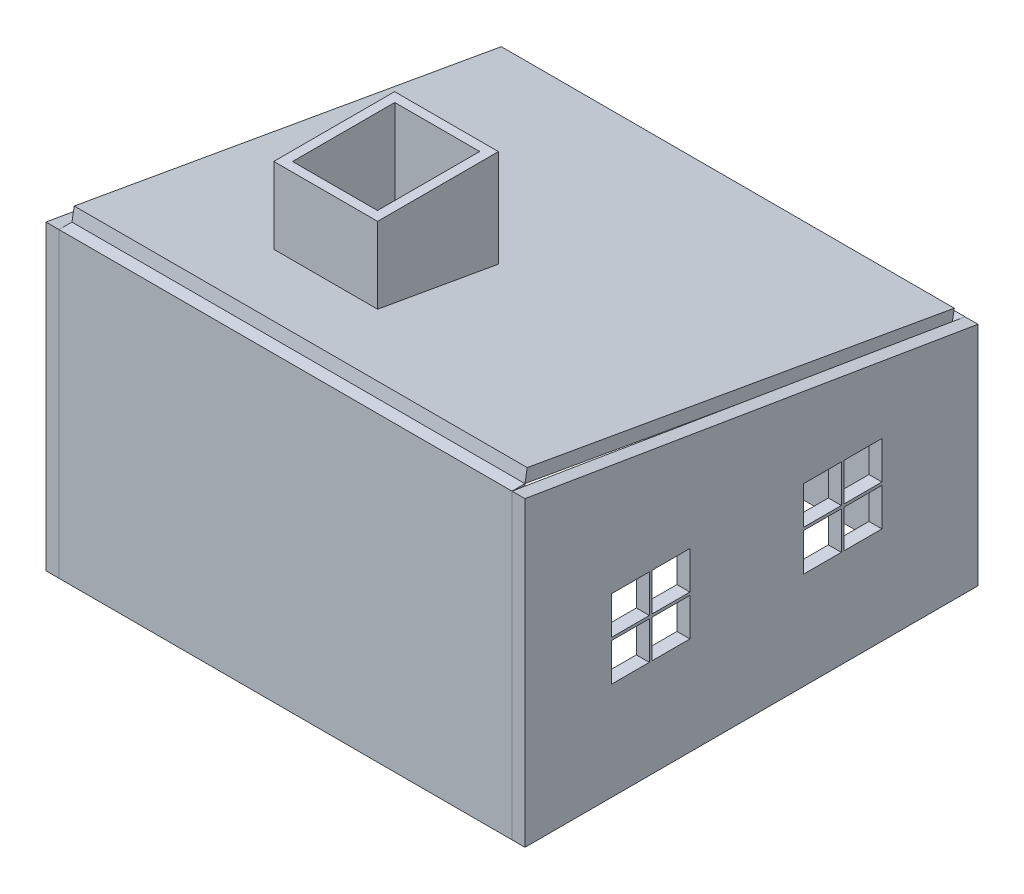
SolidWorks part; units mm, degrees
ref_plane "Front Plane" through (0, 0, 0) normal (0, 0, 1) x (1, 0, 0)
ref_plane "Top Plane" through (0, 0, 0) normal (0, 1, 0) x (1, 0, 0)
ref_plane "Right Plane" through (0, 0, 0) normal (1, 0, 0) x (0, 0, -1)
sketch "Sketch2" plane through (0, 0, 0) normal (0, 1, 0) x (1, 0, 0)
  line L1 (304.8, -287.3375) -> (-304.8, -287.3375)
  line L2 (304.8, -287.3375) -> (304.8, 287.3375)
  line L3 (304.8, 287.3375) -> (-304.8, 287.3375)
  line L4 (-304.8, -287.3375) -> (-304.8, 287.3375)
  line L5 (304.8, -287.3375) -> (-304.8, 287.3375) construction
  line L6 (304.8, 287.3375) -> (-304.8, -287.3375) construction
  point P0 (0, 0)
  dimension "D1" = 609.6
  dimension "D2" = 574.675
ref_plane "Plane1" through (-304.8, 0, 0) normal (1, 0, 0) x (0, 0, -1)
ref_plane "Plane2" through (0, 0, 287.3375) normal (0, 0, 1) x (1, 0, 0)
ref_plane "Plane3" through (304.8, 0, 0) normal (1, 0, 0) x (0, 0, -1)
ref_plane "Plane4" through (0, 0, -287.3375) normal (0, 0, 1) x (1, 0, 0)
sketch "Sketch4" plane through (0, 0, -287.3375) normal (0, 0, 1) x (1, 0, 0)
  line L1 (304.8, 0) -> (-304.8, 0)
  line L2 (304.8, 0) -> (304.8, 304.8)
  line L3 (304.8, 304.8) -> (-304.8, 304.8)
  line L4 (-304.8, 0) -> (-304.8, 304.8)
  dimension "D1" = 304.8
  dimension "D2" = 609.6
extrude "Boss-Extrude2" add sketch "Sketch4" against normal blind 17.4625 separate body contours L3 L4 L1 L2
sketch "Sketch5" plane through (-304.8, 0, 0) normal (1, 0, 0) x (0, 0, -1)
  line L1 (304.8, 0) -> (-304.8, 0)
  line L2 (304.8, 0) -> (304.8, 304.8)
  line L3 (304.8, 304.8) -> (-304.8, 406.4)
  line L4 (-304.8, 0) -> (-304.8, 406.4)
  dimension "D1" = 304.8
  dimension "D2" = 609.6
  dimension "D3" = 406.4
extrude "Boss-Extrude3" add sketch "Sketch5" against normal blind 17.4625 separate body
sketch "Sketch6" plane through (0, 0, 287.3375) normal (0, 0, 1) x (1, 0, 0)
  line L1 (-304.8, 0) -> (304.8, 0)
  line L2 (-304.8, 0) -> (-304.8, 406.4)
  line L3 (-304.8, 406.4) -> (304.8, 406.4)
  line L4 (304.8, 0) -> (304.8, 406.4)
  dimension "D1" = 609.6
  dimension "D2" = 406.4
extrude "Boss-Extrude4" add sketch "Sketch6" along normal blind 17.4625 separate body
sketch "Sketch3" plane through (304.8, 0, 0) normal (1, 0, 0) x (0, 0, -1)
  line L1 (-304.8, 0) -> (304.8, 0)
  line L2 (-304.8, 0) -> (-304.8, 406.4)
  line L3 (-304.8, 406.4) -> (304.8, 304.8)
  line L4 (304.8, 0) -> (304.8, 304.8)
  dimension "D1" = 304.8
  dimension "D2" = 609.6
extrude "Boss-Extrude1" add sketch "Sketch3" along normal blind 17.4625 separate body
ref_plane "Plane5" through (0, 344.822, -60.963) normal (0, -0.9847, 0.1741) x (-1, 0, 0)
sketch "Sketch7" plane through (0, 344.822, -60.963) normal (0, -0.9847, 0.1741) x (-1, 0, 0)
  line L0 (-304.8, 229.8851) -> (304.8, 229.8851) construction
  line L1 (304.8, -353.702) -> (-304.8, -353.702)
  line L2 (304.8, -353.702) -> (304.8, 229.8851)
  line L3 (304.8, 229.8851) -> (-304.8, 229.8851)
  line L4 (-304.8, -353.702) -> (-304.8, 229.8851)
  line L6 (-304.8, -353.702) -> (304.8, -353.702) construction
  line L7 (304.8, 229.8851) -> (0, 51.2594) construction
  line L8 (0, 51.2594) -> (-304.8, 229.8851) construction
  line L9 (0, 229.8851) -> (0, 51.2594) construction
  line L10 (0, -61.7545) -> (0, 229.8851) construction
  dimension "D1" = 609.6
extrude "Boss-Extrude6" add sketch "Sketch7" against normal blind 17.4625 separate body
ref_plane "Plane6" through (0, 508, 0) normal (0, 1, 0) x (1, 0, 0)
sketch "Sketch8" plane through (0, 362.0178, -64.0032) normal (0, 0.9847, -0.1741) x (1, 0, 0)
  line L0 (304.8, -370.8978) -> (-304.8, -370.8978) construction
  line L1 (-11.1125, -237.5478) -> (-125.4125, -237.5478)
  line L2 (-11.1125, -237.5478) -> (-11.1125, -97.8478)
  line L3 (-11.1125, -97.8478) -> (-125.4125, -97.8478)
  line L4 (-125.4125, -237.5478) -> (-125.4125, -97.8478)
  line L5 (-11.1125, -237.5478) -> (-125.4125, -97.8478) construction
  line L6 (-11.1125, -97.8478) -> (-125.4125, -237.5478) construction
  line L7 (1.5875, -85.1478) -> (-138.1125, -85.1478)
  line L8 (1.5875, -85.1478) -> (1.5875, -250.2478)
  line L9 (1.5875, -250.2478) -> (-138.1125, -250.2478)
  line L10 (-138.1125, -85.1478) -> (-138.1125, -250.2478)
  line L11 (1.5875, -85.1478) -> (-138.1125, -250.2478) construction
  line L12 (1.5875, -250.2478) -> (-138.1125, -85.1478) construction
  line L13 (-322.2625, 247.081) -> (-322.2625, -370.8978) construction
  point P0 (-68.2625, -167.6978)
  point P5 (-68.2625, -167.6978)
  dimension "D1" = 12.7
  dimension "D2" = 12.7
  dimension "D3" = 203.2
  dimension "D4" = 254
  dimension "D5" = 139.7
  dimension "D6" = 165.1
extrude "Boss-Extrude7" add sketch "Sketch8" along direction (0, 1, 0) on the side of the normal up to surface (104.6261 mm away) separate body up to plane "Plane6"
sketch "Sketch9" plane through (-322.2625, 0, 0) normal (-1, 0, 0) x (0, 0, 1)
  line L0 (76.4839, 243.6976) -> (194.6159, 243.6976)
  line L1 (-181.8749, 242.7105) -> (-63.7429, 242.7105)
  line L2 (-181.8749, 242.7105) -> (-181.8749, 124.5784)
  line L3 (-181.8749, 124.5784) -> (-63.7429, 124.5784)
  line L4 (-63.7429, 242.7105) -> (-63.7429, 124.5784)
  line L5 (-181.8749, 242.7105) -> (-63.7429, 124.5784) construction
  line L6 (-181.8749, 124.5784) -> (-63.7429, 242.7105) construction
  line L7 (-150.1249, 156.3284) -> (-95.4929, 156.3284) construction
  line L8 (-150.1249, 156.3284) -> (-150.1249, 210.9605) construction
  line L9 (-150.1249, 210.9605) -> (-95.4929, 210.9605) construction
  line L10 (-95.4929, 156.3284) -> (-95.4929, 210.9605) construction
  line L11 (-150.1249, 156.3284) -> (-95.4929, 210.9605) construction
  line L12 (-150.1249, 210.9605) -> (-95.4929, 156.3284) construction
  line L13 (-175.5249, 185.5605) -> (-124.7249, 185.5605)
  line L14 (-175.5249, 185.5605) -> (-175.5249, 236.3605)
  line L15 (-175.5249, 236.3605) -> (-124.7249, 236.3605)
  line L16 (-124.7249, 185.5605) -> (-124.7249, 236.3605)
  line L17 (-175.5249, 185.5605) -> (-124.7249, 236.3605) construction
  line L18 (-175.5249, 236.3605) -> (-124.7249, 185.5605) construction
  line L19 (-120.8929, 185.5605) -> (-70.0929, 185.5605)
  line L20 (-120.8929, 185.5605) -> (-120.8929, 236.3605)
  line L21 (-120.8929, 236.3605) -> (-70.0929, 236.3605)
  line L22 (-70.0929, 185.5605) -> (-70.0929, 236.3605)
  line L23 (-120.8929, 185.5605) -> (-70.0929, 236.3605) construction
  line L24 (-120.8929, 236.3605) -> (-70.0929, 185.5605) construction
  line L25 (-120.8929, 181.7284) -> (-70.0929, 181.7284)
  line L26 (-120.8929, 181.7284) -> (-120.8929, 130.9284)
  line L27 (-120.8929, 130.9284) -> (-70.0929, 130.9284)
  line L28 (-70.0929, 181.7284) -> (-70.0929, 130.9284)
  line L29 (-120.8929, 181.7284) -> (-70.0929, 130.9284) construction
  line L30 (-120.8929, 130.9284) -> (-70.0929, 181.7284) construction
  line L31 (-124.7249, 181.7284) -> (-175.5249, 181.7284)
  line L32 (-124.7249, 181.7284) -> (-124.7249, 130.9284)
  line L33 (-124.7249, 130.9284) -> (-175.5249, 130.9284)
  line L34 (-175.5249, 181.7284) -> (-175.5249, 130.9284)
  line L35 (-124.7249, 181.7284) -> (-175.5249, 130.9284) construction
  line L36 (-124.7249, 130.9284) -> (-175.5249, 181.7284) construction
  line L37 (76.4839, 243.6976) -> (76.4839, 125.5656)
  line L38 (76.4839, 125.5656) -> (194.6159, 125.5656)
  line L39 (194.6159, 243.6976) -> (194.6159, 125.5656)
  line L40 (76.4839, 243.6976) -> (194.6159, 125.5656) construction
  line L41 (76.4839, 125.5656) -> (194.6159, 243.6976) construction
  line L42 (108.2339, 157.3156) -> (162.8659, 157.3156) construction
  line L43 (108.2339, 157.3156) -> (108.2339, 211.9476) construction
  line L44 (108.2339, 211.9476) -> (162.8659, 211.9476) construction
  line L45 (162.8659, 157.3156) -> (162.8659, 211.9476) construction
  line L46 (108.2339, 157.3156) -> (162.8659, 211.9476) construction
  line L47 (108.2339, 211.9476) -> (162.8659, 157.3156) construction
  line L48 (82.8339, 186.5476) -> (133.6339, 186.5476)
  line L49 (82.8339, 186.5476) -> (82.8339, 237.3476)
  line L50 (82.8339, 237.3476) -> (133.6339, 237.3476)
  line L51 (133.6339, 186.5476) -> (133.6339, 237.3476)
  line L52 (82.8339, 186.5476) -> (133.6339, 237.3476) construction
  line L53 (82.8339, 237.3476) -> (133.6339, 186.5476) construction
  line L54 (137.4659, 186.5476) -> (188.2659, 186.5476)
  line L55 (137.4659, 186.5476) -> (137.4659, 237.3476)
  line L56 (137.4659, 237.3476) -> (188.2659, 237.3476)
  line L57 (188.2659, 186.5476) -> (188.2659, 237.3476)
  line L58 (137.4659, 186.5476) -> (188.2659, 237.3476) construction
  line L59 (137.4659, 237.3476) -> (188.2659, 186.5476) construction
  line L60 (137.4659, 182.7156) -> (188.2659, 182.7156)
  line L61 (137.4659, 182.7156) -> (137.4659, 131.9156)
  line L62 (137.4659, 131.9156) -> (188.2659, 131.9156)
  line L63 (188.2659, 182.7156) -> (188.2659, 131.9156)
  line L64 (137.4659, 182.7156) -> (188.2659, 131.9156) construction
  line L65 (137.4659, 131.9156) -> (188.2659, 182.7156) construction
  line L66 (133.6339, 182.7156) -> (82.8339, 182.7156)
  line L67 (133.6339, 182.7156) -> (133.6339, 131.9156)
  line L68 (133.6339, 131.9156) -> (82.8339, 131.9156)
  line L69 (82.8339, 182.7156) -> (82.8339, 131.9156)
  line L70 (133.6339, 182.7156) -> (82.8339, 131.9156) construction
  line L71 (133.6339, 131.9156) -> (82.8339, 182.7156) construction
  point P0 (-122.8089, 183.6445)
  point P5 (-122.8089, 183.6445)
  point P26 (135.5499, 184.6316)
  point P31 (135.5499, 184.6316)
  dimension "D1" = 50.8
  dimension "D2" = 6.35
  dimension "D3" = 6.35
  dimension "D4" = 6.35
extrude "Cut-Extrude1" cut sketch "Sketch9" against normal through all contours L13 L16 L15 L14 | L31 L34 L33 L32 | L19 L22 L21 L20 | L28 L25 L26 L27 | L66 L69 L68 L67 | L48 L51 L50 L49 | L54 L57 L56 L55 | L63 L60 L61 L62
sketch "Sketch10" plane through (0, 0, -304.8) normal (0, 0, -1) x (-1, 0, 0)
  line L0 (-304.8, 0) -> (304.8, 0) construction
  line L1 (-50.8, 0) -> (50.8, 0)
  line L2 (-50.8, 0) -> (-50.8, 165.1)
  line L3 (-50.8, 165.1) -> (50.8, 165.1)
  line L4 (50.8, 0) -> (50.8, 165.1)
  line L5 (-50.8, 165.1) -> (0, 0) construction
  line L6 (0, 0) -> (50.8, 165.1) construction
  dimension "D1" = 101.6
  dimension "D2" = 165.1
extrude "Boss-Extrude8" add sketch "Sketch10" along normal blind 17.4625 separate body
sketch "Sketch11" plane through (0, 0, -322.2625) normal (0, 0, -1) x (-1, 0, 0)
  line L0 (-50.8, 165.1) -> (50.8, 0) construction
  line L2 (-25.4, 38.1) -> (25.4, 38.1) construction
  line L3 (-25.4, 38.1) -> (-25.4, 127) construction
  line L4 (-25.4, 127) -> (25.4, 127) construction
  line L5 (25.4, 38.1) -> (25.4, 127) construction
  line L6 (-25.4, 38.1) -> (25.4, 127) construction
  line L7 (-25.4, 127) -> (25.4, 38.1) construction
  line L8 (-34.925, 107.95) -> (-15.875, 107.95)
  line L9 (-34.925, 107.95) -> (-34.925, 146.05)
  line L10 (-34.925, 146.05) -> (-15.875, 146.05)
  line L11 (-15.875, 107.95) -> (-15.875, 146.05)
  line L12 (-34.925, 107.95) -> (-15.875, 146.05) construction
  line L13 (-34.925, 146.05) -> (-15.875, 107.95) construction
  line L14 (15.875, 107.95) -> (34.925, 107.95)
  line L15 (15.875, 107.95) -> (15.875, 146.05)
  line L16 (15.875, 146.05) -> (34.925, 146.05)
  line L17 (34.925, 107.95) -> (34.925, 146.05)
  line L18 (15.875, 107.95) -> (34.925, 146.05) construction
  line L19 (15.875, 146.05) -> (34.925, 107.95) construction
  line L20 (34.925, 57.15) -> (15.875, 57.15)
  line L21 (34.925, 57.15) -> (34.925, 19.05)
  line L22 (34.925, 19.05) -> (15.875, 19.05)
  line L23 (15.875, 57.15) -> (15.875, 19.05)
  line L24 (34.925, 57.15) -> (15.875, 19.05) construction
  line L25 (34.925, 19.05) -> (15.875, 57.15) construction
  line L26 (-15.875, 57.15) -> (-34.925, 57.15)
  line L27 (-15.875, 57.15) -> (-15.875, 19.05)
  line L28 (-15.875, 19.05) -> (-34.925, 19.05)
  line L29 (-34.925, 57.15) -> (-34.925, 19.05)
  line L30 (-15.875, 57.15) -> (-34.925, 19.05) construction
  line L31 (-15.875, 19.05) -> (-34.925, 57.15) construction
  point P4 (0, 82.55)
  point P5 (0, 82.55)
  dimension "D1" = 88.9
  dimension "D2" = 50.8
  dimension "D3" = 38.1
  dimension "D4" = 19.05
extrude "Cut-Extrude2" cut sketch "Sketch11" against normal blind 8.7312 flip side to cut
chamfer "Chamfer1" distance 3.175 angle 45 16 edges at (25.4, 57.15, -322.2625) (15.875, 38.1, -322.2625) (25.4, 19.05, -322.2625) (34.925, 38.1, -322.2625) (-25.4, 57.15, -322.2625) (-34.925, 38.1, -322.2625) (-25.4, 19.05, -322.2625) (-15.875, 38.1, -322.2625) (-25.4, 107.95, -322.2625) (-15.875, 127, -322.2625) (-25.4, 146.05, -322.2625) (-34.925, 127, -322.2625) (25.4, 107.95, -322.2625) (34.925, 127, -322.2625) (25.4, 146.05, -322.2625) (15.875, 127, -322.2625)
